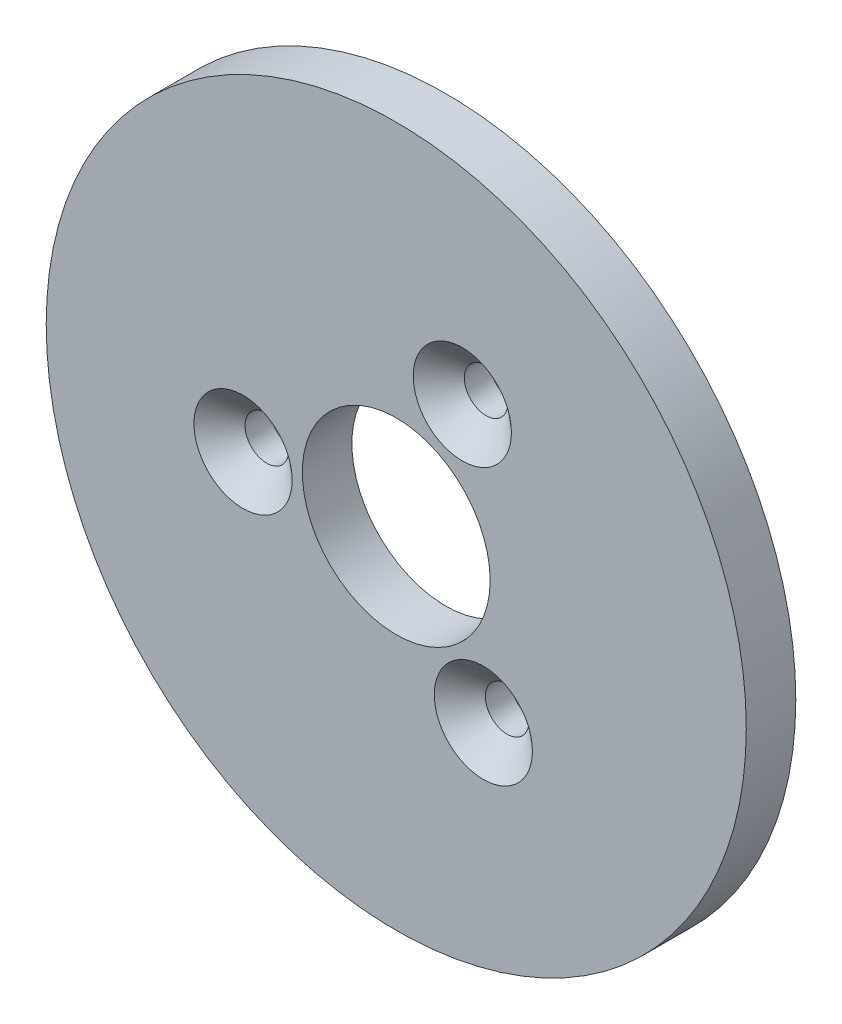
SolidWorks part; units mm, degrees
ref_plane "Front Plane" through (0, 0, 0) normal (0, 0, 1) x (1, 0, 0)
ref_plane "Top Plane" through (0, 0, 0) normal (0, 1, 0) x (1, 0, 0)
ref_plane "Right Plane" through (0, 0, 0) normal (1, 0, 0) x (0, 0, -1)
sketch "Sketch1" plane through (0, 0, 0) normal (0, 0, 1) x (1, 0, 0)
  circle A0 centre (0, 0) radius 20.5
  dimension "D1" = 41
extrude "Boss-Extrude1" add sketch "Sketch1" along normal blind 2.9
sketch "Sketch2" plane through (0, 0, 2.9) normal (0, 0, 1) x (1, 0, 0)
  circle A3 centre (-8.9719, -0.7111) radius 1.275
  circle A4 centre (-8.9719, -0.7111) radius 1.275
  circle A5 centre (5.1018, -7.4143) radius 1.275
  circle A6 centre (5.1018, -7.4143) radius 1.275
  circle A7 centre (3.8701, 8.1254) radius 1.275
  circle A8 centre (3.8701, 8.1254) radius 1.275
  dimension "D2" = 0
  dimension "D3" = 0
  dimension "D4" = 0
extrude "Cut-Extrude1" cut sketch "Sketch2" against normal through all
chamfer "Chamfer1" distance 1.6 angle 41 3 edges at (-7.6969, -0.7111, 2.9) (5.1451, 8.1254, 2.9) (6.3768, -7.4143, 2.9)
sketch "Sketch3" plane through (0, 0, 2.9) normal (0, 0, 1) x (1, 0, 0)
  circle A1 centre (0, 0) radius 5.5
  circle A2 centre (0, 0) radius 5.5
  dimension "D1" = 0
extrude "Cut-Extrude2" cut sketch "Sketch3" against normal through all
equation "\"smallPulleyTeeth\"= 15"
equation "\"largePulleyTeeth\"= 30"
equation "\"eighthThick\"= 2.9mm"
equation "\"sixteenthThick\"= 1.7mm"
equation "\"quarterThick\"=5.9mm"
equation "\"OD\"= 145mm"
equation "\"puckAngle\"= 60.5deg"
equation "\"puckDiam\"= 76.5mm"
equation "\"axlePress\"= 5.9mm"
equation "\"press\"= 0.2mm"
equation "\"wheelClear\"= 0.3mm"
equation "\"10-32clear\"= 4.5mm"
equation "\"D1@Boss-Extrude1\"=\"eighthThick\""
equation "\"D1@Chamfer1\"=(6.5-\"6-32clear\")/2"
equation "\"6-32clear\"= 3.3mm"
equation "\"8-32clear\"= 4.0mm"
